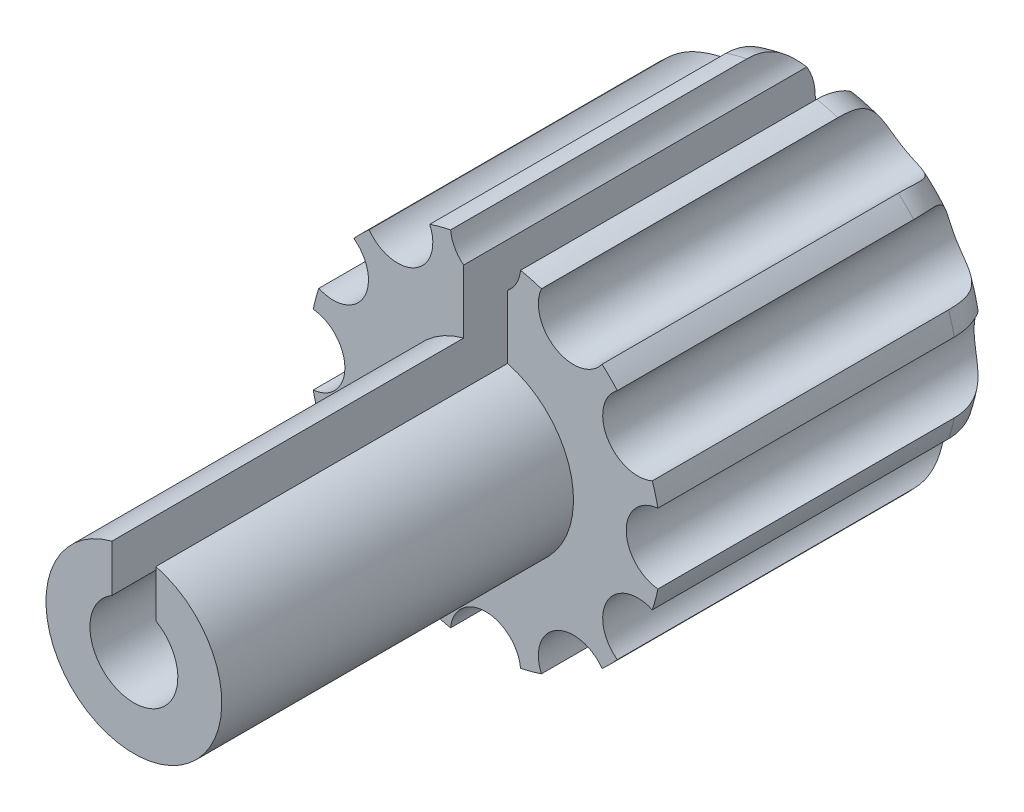
SolidWorks part; units mm, degrees
material "Aleación 1060"
ref_plane "Alzado" through (0, 0, 0) normal (0, 0, 1) x (1, 0, 0)
ref_plane "Planta" through (0, 0, 0) normal (0, 1, 0) x (1, 0, 0)
ref_plane "Vista lateral" through (0, 0, 0) normal (1, 0, 0) x (0, 0, -1)
sketch "Croquis1" plane through (0, 0, 0) normal (0, 0, 1) x (1, 0, 0)
  circle A0 centre (0, 0) radius 6.35
  dimension "D1" = 12.7
extrude "Saliente-Extruir1" add sketch "Croquis1" along normal blind 12.7
fillet "Redondeo2" radius 2 1 edges at (6.35, 0, 0)
sketch "Croquis2" plane through (0, 0, 12.7) normal (0, 0, 1) x (1, 0, 0)
  line L0 (0, 0) -> (-6.35, 0) construction
  circle A1 centre (-6.35, 0) radius 1.27
  circle A2 centre (-5.4993, 3.175) radius 1.27
  circle A3 centre (-3.175, 5.4993) radius 1.27
  circle A4 centre (0, 6.35) radius 1.27
  circle A5 centre (3.175, 5.4993) radius 1.27
  circle A6 centre (5.4993, 3.175) radius 1.27
  circle A7 centre (6.35, 0) radius 1.27
  circle A8 centre (5.4993, -3.175) radius 1.27
  circle A9 centre (3.175, -5.4993) radius 1.27
  circle A10 centre (0, -6.35) radius 1.27
  circle A11 centre (-3.175, -5.4993) radius 1.27
  circle A12 centre (-5.4993, -3.175) radius 1.27
  point P30 (0, 0)
  dimension "D2" = 2.54
  dimension "D1" = 6.35
  dimension "D3" = 12
extrude "Cortar-Extruir1" cut sketch "Croquis2" against normal blind 12.7
sketch "Croquis3" plane through (0, 0, 0) normal (0, 0, -1) x (-1, 0, 0)
  circle A0 centre (0, 0) radius 1.5875
  dimension "D1" = 3.175
sketch "Croquis4" plane through (0, 0, 12.7) normal (0, 0, 1) x (1, 0, 0)
  circle A0 centre (0, 0) radius 3.175
  dimension "D1" = 6.35
extrude "Saliente-Extruir2" add sketch "Croquis4" along normal blind 12.7
extrude "Cortar-Extruir2" cut sketch "Croquis3" against normal through all
sketch "Croquis5" plane through (0, 0, 0) normal (0, 1, 0) x (1, 0, 0)
  line L0 (0, -25.4) -> (0, 0) construction
  line L1 (-3.175, -25.4) -> (3.175, -25.4) construction
  line L2 (0.7937, 0) -> (-0.7937, 0)
  line L3 (1.5875, 0) -> (-1.5875, 0) construction
  line L4 (-0.7937, 0) -> (-0.7937, -31.2548)
  line L5 (-0.7937, -31.2548) -> (0.7937, -31.2548)
  line L6 (0.7937, 0) -> (0.7937, -31.2548)
  point P12 (0, -31.2548)
  dimension "D1" = 0.7937
extrude "Cortar-Extruir3" cut sketch "Croquis5" along normal blind 12.7
